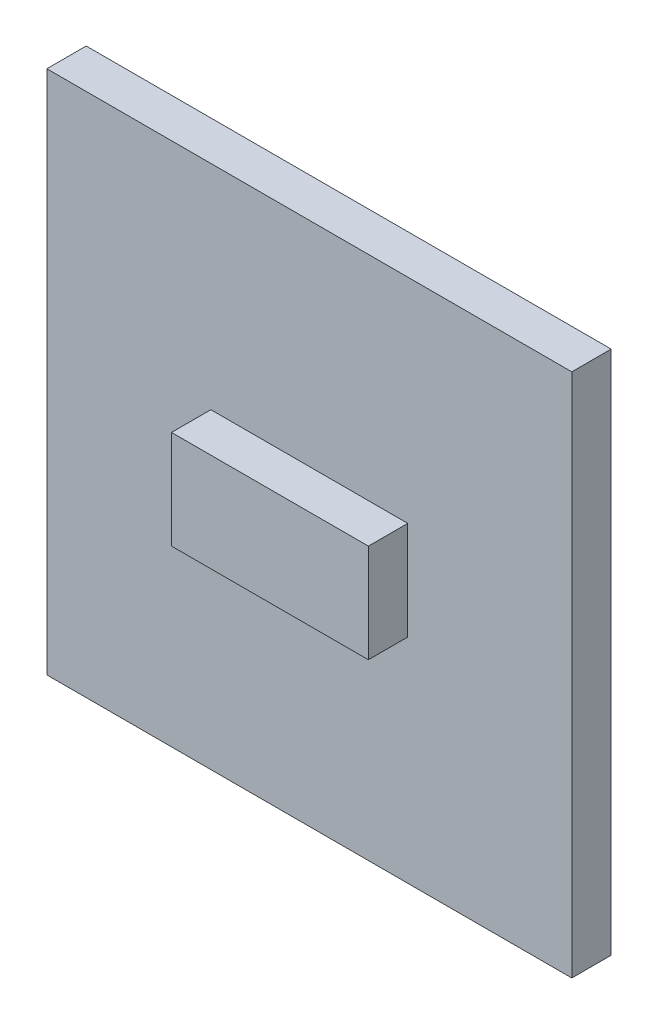
SolidWorks part; units mm, degrees
ref_plane "Front Plane" through (0, 0, 0) normal (0, 0, 1) x (1, 0, 0)
ref_plane "Top Plane" through (0, 0, 0) normal (0, 1, 0) x (1, 0, 0)
ref_plane "Right Plane" through (0, 0, 0) normal (1, 0, 0) x (0, 0, -1)
sketch "Sketch1" plane through (0, 0, 0) normal (0, 0, 1) x (1, 0, 0)
  line L1 (0, 0) -> (16, 0)
  line L2 (0, 0) -> (0, -16)
  line L3 (0, -16) -> (16, -16)
  line L4 (16, 0) -> (16, -16)
  point P4 (11.1458, -6.2926)
  point P5 (0, 0)
  dimension "D1" = 16
extrude "Boss-Extrude1" add sketch "Sketch1" along normal blind 1.2
sketch "Sketch2" plane through (0, 0, 1.2) normal (0, 0, 1) x (1, 0, 0)
  line L0 (16, 0) -> (0, 0) construction
  line L1 (5, -6.5) -> (11, -6.5)
  line L2 (5, -6.5) -> (5, -9.5)
  line L3 (5, -9.5) -> (11, -9.5)
  line L4 (11, -6.5) -> (11, -9.5)
  line L5 (16, -16) -> (16, 0) construction
  point P4 (8, -6.5)
  point P7 (8, 0)
  point P8 (11, -8)
  point P11 (16, -8)
  dimension "D1" = 6
  dimension "D2" = 3
extrude "Boss-Extrude2" add sketch "Sketch2" along normal blind 1.2
